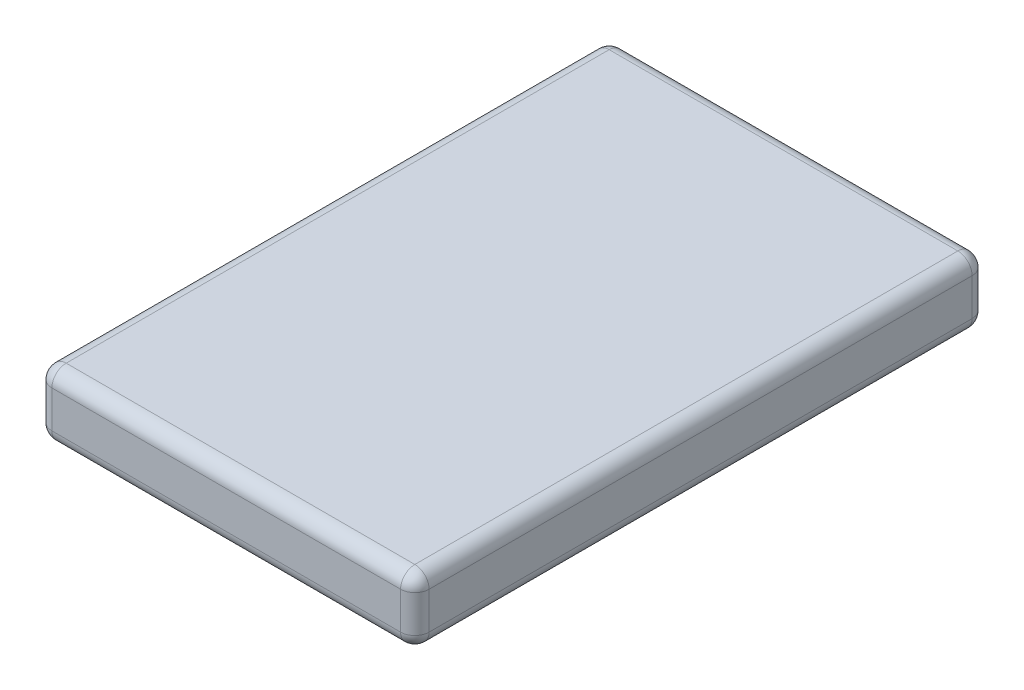
SolidWorks part; units mm, degrees
ref_plane "Front Plane" through (0, 0, 0) normal (0, 0, 1) x (1, 0, 0)
ref_plane "Top Plane" through (0, 0, 0) normal (0, 1, 0) x (1, 0, 0)
ref_plane "Right Plane" through (0, 0, 0) normal (1, 0, 0) x (0, 0, -1)
sketch "Sketch1" plane through (0, 0, 0) normal (0, 1, 0) x (1, 0, 0)
  line L1 (0, 0) -> (33.528, 0)
  line L2 (0, 0) -> (0, 50.8)
  line L3 (0, 50.8) -> (33.528, 50.8)
  line L4 (33.528, 0) -> (33.528, 50.8)
  dimension "D1" = 50.8
  dimension "D2" = 33.528
extrude "Boss-Extrude1" add sketch "Sketch1" along normal blind 5.842
fillet "Fillet1" radius 1.27 12 edges at (33.528, 2.921, -50.8) (16.764, 5.842, -50.8) (0, 2.921, -50.8) (16.764, 0, -50.8) (0, 5.842, -25.4) (0, 0, -25.4) (33.528, 2.921, 0) (33.528, 0, -25.4) (33.528, 5.842, -25.4) (0, 2.921, 0) (16.764, 0, 0) (16.764, 5.842, 0)
